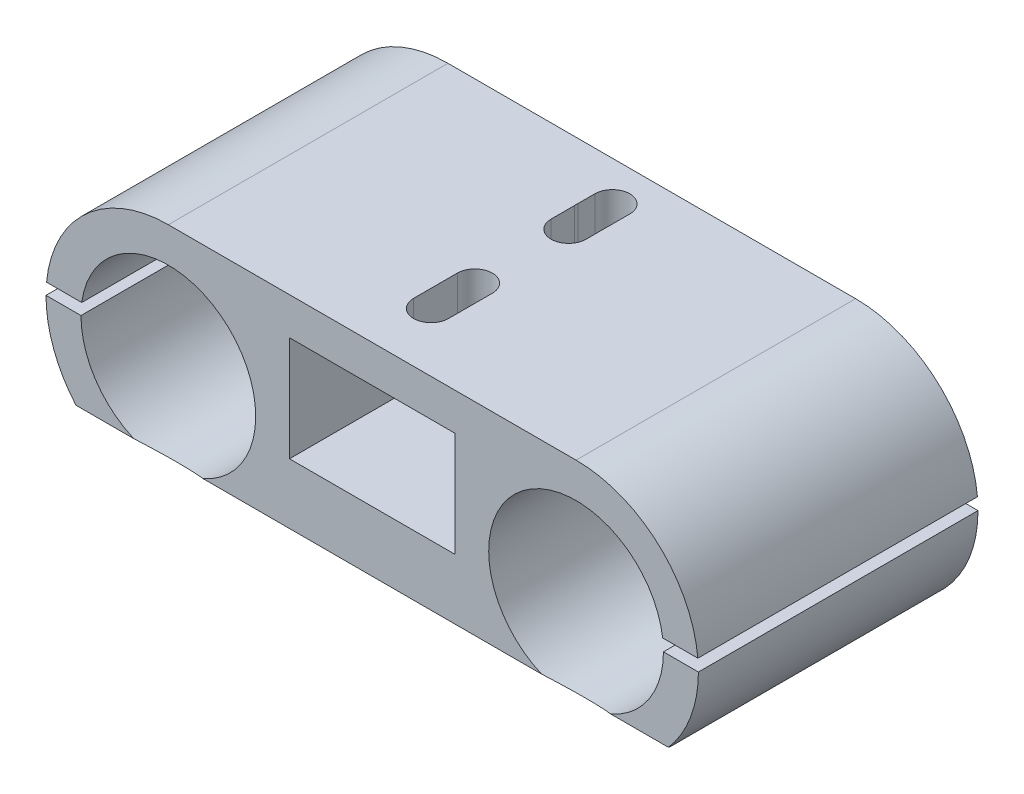
SolidWorks part; units mm, degrees
ref_plane "Front Plane" through (0, 0, 0) normal (0, 0, 1) x (1, 0, 0)
ref_plane "Top Plane" through (0, 0, 0) normal (0, 1, 0) x (1, 0, 0)
ref_plane "Right Plane" through (0, 0, 0) normal (1, 0, 0) x (0, 0, -1)
sketch "Sketch2" plane through (0, 0, 0) normal (0, 0, 1) x (1, 0, 0)
  line L0 (-17.5, 4.7671) -> (17.5, 4.7671) construction
  line L7 (-17.5, -5.7329) -> (-5, -5.7329)
  line L23 (-5, -5.7329) -> (17.5, -5.7329)
  line L24 (17.5, 15.2671) -> (-17.5, 15.2671)
  circle A0 centre (-17.5, 4.7671) radius 7.5
  circle A1 centre (17.5, 4.7671) radius 7.5
  arc A2 (-17.5, 15.2671) -> (-17.5, -5.7329) centre (-17.5, 4.7671) ccw
  arc A3 (17.5, -5.7329) -> (17.5, 15.2671) centre (17.5, 4.7671) ccw
  point P0 (0, 0)
  point P10 (0, 4.7671)
  dimension "D1" = 15
  dimension "D3" = 3
  dimension "D2" = 35
extrude "Boss-Extrude1" add sketch "Sketch2" along normal blind 24
sketch "Sketch5" plane through (0, 0, 0) normal (0, 0, -1) x (-1, 0, 0)
  line L0 (17.5, -5.7329) -> (-17.5, -5.7329) construction
  line L1 (-40.158, -5.7329) -> (28.4592, -5.7329)
  line L2 (-40.158, -5.7329) -> (-40.158, -4.7329)
  line L3 (-40.158, -4.7329) -> (28.4592, -4.7329)
  line L4 (28.4592, -5.7329) -> (28.4592, -4.7329)
  dimension "D1" = 1
extrude "Cut-Extrude2" cut sketch "Sketch5" against normal through all both and the other way through all
sketch "Sketch6" plane through (0, 0, 0) normal (0, 0, -1) x (-1, 0, 0)
  line L0 (-21.9721, -4.7329) -> (21.9721, -4.7329) construction
  line L1 (-7.1, 3.0671) -> (7.1, 3.0671)
  line L2 (-7.1, 3.0671) -> (-7.1, 12.0671)
  line L3 (-7.1, 12.0671) -> (7.1, 12.0671)
  line L4 (7.1, 3.0671) -> (7.1, 12.0671)
  point P4 (0, 3.0671)
  dimension "D1" = 14.2
  dimension "D2" = 9
  dimension "D3" = 7.8
extrude "Cut-Extrude4" cut sketch "Sketch6" against normal through all
sketch "Sketch7" plane through (0, 15.2671, 0) normal (0, 1, 0) x (1, 0, 0)
  line L0 (17.5, 0) -> (-17.5, 0) construction
  circle A0 centre (0, -5) radius 1.5
  circle A1 centre (0, -17) radius 1.5
  point P7 (0, 0)
  dimension "D1" = 3
  dimension "D2" = 12
  dimension "D3" = 5
extrude "Cut-Extrude5" cut sketch "Sketch7" against normal blind 7
sketch "Sketch8" plane through (0, 0, 0) normal (1, 0, 0) x (0, 0, -1)
  line L0 (-26.4753, 0) -> (-18.9328, -6.4566)
  line L1 (-18.9328, -6.4566) -> (-28.3872, -5.9216)
  line L2 (-28.3872, -5.9216) -> (-26.4753, 0)
extrude "Cut-Extrude6" cut sketch "Sketch8" against normal through all both and the other way through all
ref_plane "Plane1" through (30, 0, 0) normal (1, 0, 0) x (0, 0, -1)
sketch "Sketch9" plane through (30, 0, 0) normal (1, 0, 0) x (0, 0, -1)
  line L0 (0, -4.7329) -> (0, 15.2671) construction
  line L1 (-29.5516, 4.7671) -> (4.0179, 4.7671)
  line L2 (-29.5516, 4.7671) -> (-29.5516, 5.7671)
  line L3 (-29.5516, 5.7671) -> (4.0179, 5.7671)
  line L4 (4.0179, 4.7671) -> (4.0179, 5.7671)
  line L5 (-29.5516, 4.7671) -> (4.0179, 5.7671) construction
  line L6 (-29.5516, 5.7671) -> (4.0179, 4.7671) construction
  point P0 (-12.7669, 5.2671)
  point P7 (0, 5.2671)
  point P8 (4.0179, 5.2671)
  dimension "D1" = 1
extrude "Cut-Extrude7" cut sketch "Sketch9" against normal blind 10
mirror "Mirror1" about plane through (0, 0, 0) normal (1, 0, 0) of "Cut-Extrude7"
sketch "Sketch11" plane through (0, 15.2671, 0) normal (0, 1, 0) x (1, 0, 0)
  line L0 (0, -18.9446) -> (0, -15.1892) construction
  line L1 (-1.5, -18.9446) -> (-1.5, -15.1892)
  line L2 (1.5, -18.9446) -> (1.5, -15.1892)
  line L3 (0.0076, -7.1498) -> (0.0076, -3.3943) construction
  line L4 (-1.4924, -7.1498) -> (-1.4924, -3.3943)
  line L5 (1.5076, -7.1498) -> (1.5076, -3.3943)
  arc A0 (-1.5, -18.9446) -> (1.5, -18.9446) centre (0, -18.9446) ccw
  arc A1 (1.5, -15.1892) -> (-1.5, -15.1892) centre (0, -15.1892) ccw
  arc A2 (-1.4924, -7.1498) -> (1.5076, -7.1498) centre (0.0076, -7.1498) ccw
  arc A3 (1.5076, -3.3943) -> (-1.4924, -3.3943) centre (0.0076, -3.3943) ccw
  point P3 (0, -17.0669)
  point P8 (0, -17.0669)
  point P11 (0.0076, -5.272)
  dimension "D1" = 3
extrude "Cut-Extrude8" cut sketch "Sketch11" against normal blind 6 and the other way through all
